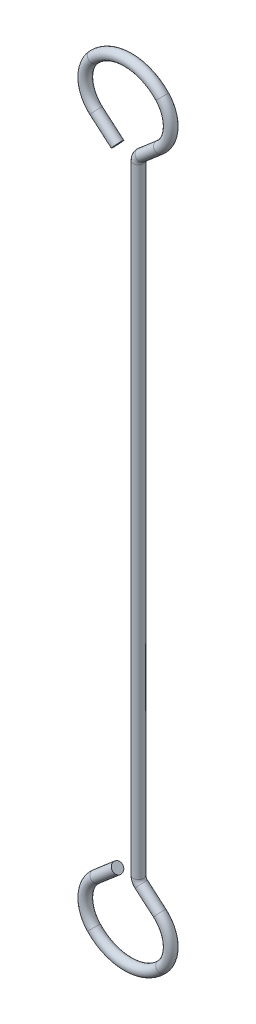
SolidWorks part; units mm, degrees
ref_plane "Front Plane" through (0, 0, 0) normal (0, 0, 1) x (1, 0, 0)
ref_plane "Top Plane" through (0, 0, 0) normal (0, 1, 0) x (1, 0, 0)
ref_plane "Right Plane" through (0, 0, 0) normal (1, 0, 0) x (0, 0, -1)
sketch "Sketch1" plane through (0, 0, 0) normal (0, 0, 1) x (1, 0, 0)
  line L0 (0, 7.408) -> (0, -7.408)
  line L1 (0.0698, 7.5599) -> (0.5109, 7.9379)
  line L2 (-1.0109, 7.9379) -> (-0.5, 7.5)
  line L3 (-0.25, 8.25) -> (-0.25, 7.5) construction
  line L4 (-0.5, 7.5) -> (0, 7.5) construction
  line L5 (0.5109, 7.9379) -> (0.875, 8.25) construction
  line L6 (-1.375, 8.25) -> (-1.0109, 7.9379) construction
  line L7 (0, 0) -> (-5.4158, 0) construction
  line L8 (0.0698, -7.5599) -> (0.5109, -7.9379)
  line L9 (-1.0109, -7.9379) -> (-0.5, -7.5)
  arc A0 (0.5683, 9.022) -> (-1.0683, 9.022) centre (-0.25, 8.25) ccw
  arc A1 (0.5109, 7.9379) -> (0.5683, 9.022) centre (0.0228, 8.5073) ccw
  arc A2 (-1.0683, 9.022) -> (-1.0109, 7.9379) centre (-0.5228, 8.5073) ccw
  arc A3 (0.875, 8.25) -> (0.5683, 9.022) centre (-0.25, 8.25) ccw construction
  arc A4 (-1.0683, 9.022) -> (-1.375, 8.25) centre (-0.25, 8.25) ccw construction
  arc A5 (0.5109, -7.9379) -> (0.5683, -9.022) centre (0.0228, -8.5073) cw
  arc A6 (0.5683, -9.022) -> (-1.0683, -9.022) centre (-0.25, -8.25) cw
  arc A7 (-1.0683, -9.022) -> (-1.0109, -7.9379) centre (-0.5228, -8.5073) cw
  arc A8 (0.0698, 7.5599) -> (0, 7.408) centre (0.2, 7.408) ccw
  arc A9 (0, -7.408) -> (0.0698, -7.5599) centre (0.2, -7.408) ccw
  point P29 (0, -7.5)
  dimension "D4" = 2.25
  dimension "D7" = 0.75
  dimension "D5" = 0.2
  dimension "D1" = 15
  dimension "D3" = 0.75
  dimension "D6" = 0.5
sweep "Sweep1" add path "Sketch1" circular profile diameter 0.25 parameters "D3"=0.25
ref_plane "Plane1" through (0, 0, 0.125) normal (0, 0, 1) x (1, 0, 0)
equation "\"D1@Plane1\" = \"D3@Sweep1\" / 2"
equation "\"D3@Sweep1\"=\"sweep\""
